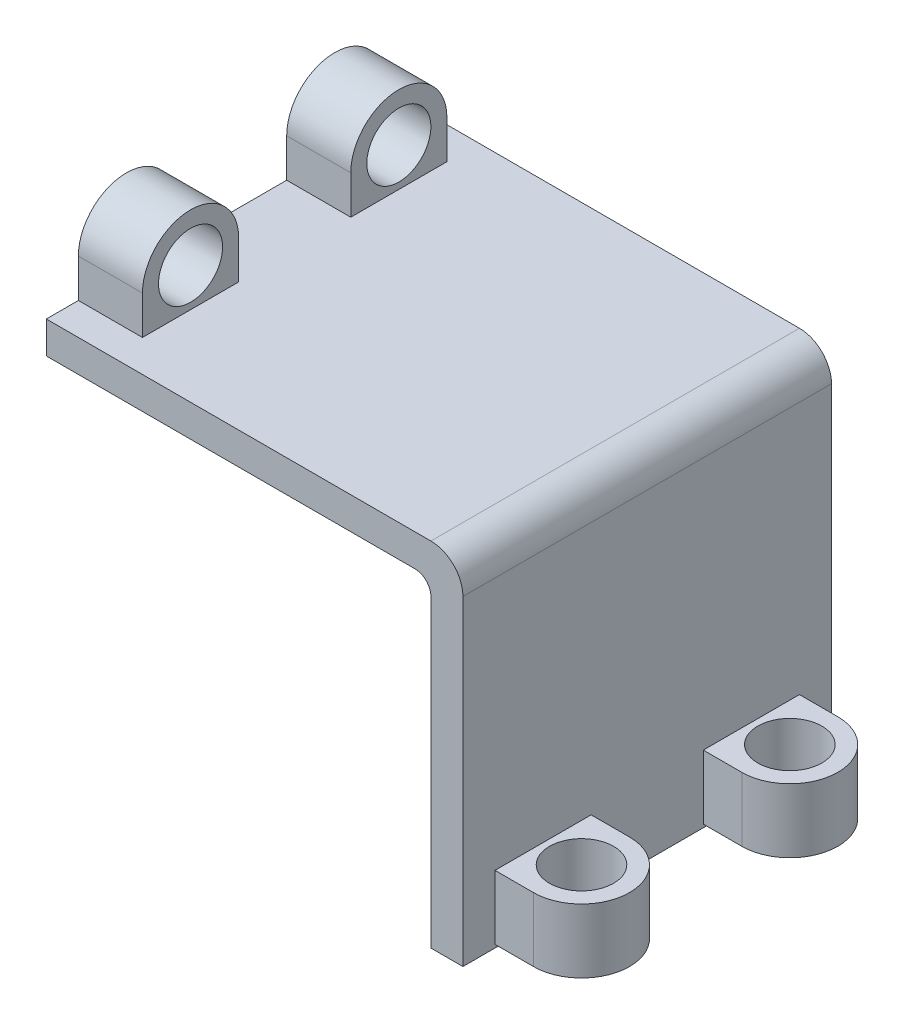
SolidWorks part; units mm, degrees
ref_plane "Front Plane" through (0, 0, 0) normal (0, 0, 1) x (1, 0, 0)
ref_plane "Top Plane" through (0, 0, 0) normal (0, 1, 0) x (1, 0, 0)
ref_plane "Right Plane" through (0, 0, 0) normal (1, 0, 0) x (0, 0, -1)
sketch "Sketch1" plane through (0, 0, 0) normal (0, 0, 1) x (1, 0, 0)
  line L0 (0, 0) -> (1, 0)
  line L1 (1, 0) -> (1, 10)
  line L2 (0, 11) -> (-12, 11)
  line L3 (-12, 11) -> (-12, 10)
  line L4 (-12, 10) -> (-0.5, 10)
  line L5 (0, 9.5) -> (0, 0)
  arc A0 (1, 10) -> (0, 11) centre (0, 10) ccw
  arc A1 (0, 9.5) -> (-0.5, 10) centre (-0.5, 9.5) ccw
  point P15 (0, 10)
  dimension "D5" = 1
  dimension "D6" = 0.5
  dimension "D1" = 1
  dimension "D2" = 1
  dimension "D3" = 10
  dimension "D4" = 12
extrude "Boss-Extrude2" add sketch "Sketch1" along normal blind 11.5
ref_plane "Plane1" through (0, 0.1, 0) normal (0, -1, 0) x (-1, 0, 0)
sketch "Sketch3" plane through (0, 0.1, 0) normal (0, -1, 0) x (-1, 0, 0)
  line L0 (-1, 0) -> (-1, -11.5)
  line L1 (-1, -11.5) -> (-1, 0) construction
  line L2 (-1, -10.5) -> (-2.2, -10.5)
  line L3 (-2.2, -10.5) -> (-2.2, -7.5)
  line L4 (-2.2, -7.5) -> (-1, -7.5)
  line L5 (0, -11.5) -> (-1, -11.5) construction
  arc A0 (-2.2, -10.5) -> (-2.2, -7.5) centre (-2.2, -9) cw
  circle A1 centre (-2.2, -9) radius 1
  dimension "D3" = 2
  dimension "D1" = 1.2
  dimension "D2" = 3
  dimension "D4" = 1
sketch "Sketch5" plane through (-12, 0, 0) normal (-1, 0, 0) x (0, 0, 1)
  line L0 (11.5, 11) -> (0, 11)
  line L1 (10.5, 11) -> (10.5, 12.2)
  line L2 (10.5, 12.2) -> (7.5, 12.2)
  line L3 (7.5, 12.2) -> (7.5, 11)
  arc A0 (7.5, 12.2) -> (10.5, 12.2) centre (9, 12.2) cw
  circle A1 centre (9, 12.2) radius 1
  dimension "D4" = 2
  dimension "D1" = 1
  dimension "D2" = 3
  dimension "D3" = 1.2
ref_plane "Plane2" through (0, 0, 5.75) normal (0, 0, -1) x (-1, 0, 0)
extrude "Boss-Extrude5" add sketch "Sketch5" against normal blind 2 contours A1 L2 L3 L0 L1 | A1 L2 A0
extrude "Boss-Extrude6" add sketch "Sketch3" against normal blind 2 contours A1 L3 A0 | A1 L3 L2 L0 L4
mirror "Mirror1" about plane through (0, 0, 5.75) normal (0, 0, -1) of "Boss-Extrude5", "Boss-Extrude6"
